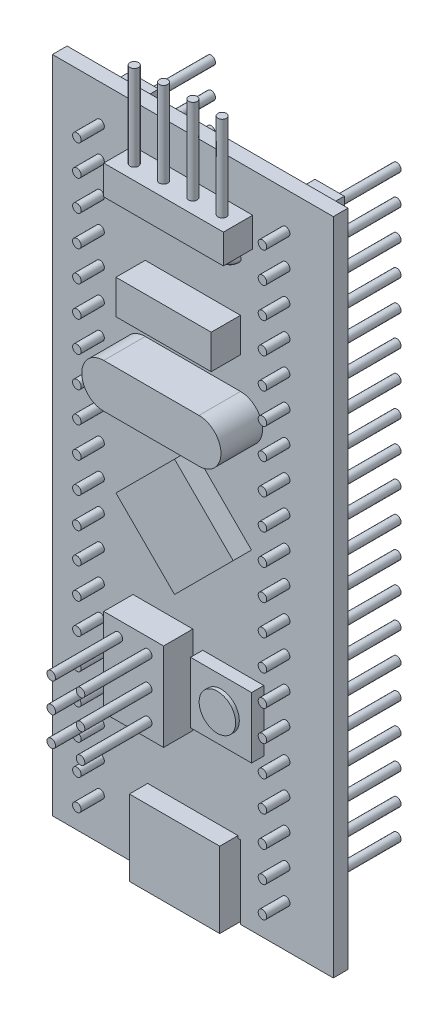
SolidWorks part; units mm, degrees
material "Плата обработки данных, простая"
ref_plane "Спереди" through (0, 0, 0) normal (0, 0, 1) x (1, 0, 0)
ref_plane "Сверху" through (0, 0, 0) normal (0, 1, 0) x (1, 0, 0)
ref_plane "Справа" through (0, 0, 0) normal (1, 0, 0) x (0, 0, -1)
sketch "Эскиз1" plane through (0, 0, 0) normal (0, 0, 1) x (1, 0, 0)
  line L0 (0.4001, -30.8708) -> (0.4001, 23.1292) construction
  line L1 (-11.0999, 23.1292) -> (11.9001, 23.1292)
  line L2 (-11.0999, 23.1292) -> (-11.0999, -30.8708)
  line L3 (-11.0999, -30.8708) -> (11.9001, -30.8708)
  line L4 (11.9001, 23.1292) -> (11.9001, -30.8708)
  line L5 (-11.0999, -3.8708) -> (11.9001, -3.8708) construction
  dimension "D1" = 23
  dimension "D2" = 54
extrude "Бобышка-Вытянуть1" add sketch "Эскиз1" along normal blind 1.2
sketch "Эскиз2" plane through (0, 0, 0) normal (0, 0, -1) x (-1, 0, 0)
  line L0 (-0.4001, 23.1292) -> (-0.4001, -30.8708) construction
  line L1 (-11.9001, 23.1292) -> (11.0999, 23.1292) construction
  line L2 (11.0999, -30.8708) -> (-11.9001, -30.8708) construction
  line L3 (-9.2001, 21.4292) -> (-9.2001, -29.1708)
  line L4 (5.9999, 21.4292) -> (8.3999, 21.4292)
  line L5 (5.9999, 21.4292) -> (5.9999, -29.1708)
  line L6 (5.9999, -29.1708) -> (8.3999, -29.1708)
  line L7 (8.3999, 21.4292) -> (8.3999, -29.1708)
  line L8 (-6.8001, -29.1708) -> (-9.2001, -29.1708)
  line L9 (-6.8001, 21.4292) -> (-6.8001, -29.1708)
  line L10 (-6.8001, 21.4292) -> (-9.2001, 21.4292)
  line L11 (-0.4001, -3.8708) -> (-7.8164, -3.8708) construction
  point P16 (-6.8001, -3.8708)
  dimension "D1" = 2.4
  dimension "D2" = 50.6
  dimension "D3" = 17.6
extrude "Бобышка-Вытянуть2" add sketch "Эскиз2" along normal blind 2.4
sketch "Эскиз3" plane through (0, 0, -2.4) normal (0, 0, -1) x (-1, 0, 0)
  circle A0 centre (-8.0001, 20.1329) radius 0.35
  circle A1 centre (7.1999, 20.1329) radius 0.35
  circle A2 centre (7.1999, 17.6329) radius 0.35
  circle A3 centre (7.1999, 15.1329) radius 0.35
  circle A4 centre (7.1999, 12.6329) radius 0.35
  circle A5 centre (7.1999, 10.1329) radius 0.35
  circle A6 centre (7.1999, 7.6329) radius 0.35
  circle A7 centre (7.1999, 5.1329) radius 0.35
  circle A8 centre (7.1999, 2.6329) radius 0.35
  circle A9 centre (7.1999, 0.1329) radius 0.35
  circle A10 centre (7.1999, -2.3671) radius 0.35
  circle A11 centre (7.1999, -4.8671) radius 0.35
  circle A12 centre (7.1999, -7.3671) radius 0.35
  circle A13 centre (7.1999, -9.8671) radius 0.35
  circle A14 centre (7.1999, -12.3671) radius 0.35
  circle A15 centre (7.1999, -14.8671) radius 0.35
  circle A16 centre (7.1999, -17.3671) radius 0.35
  circle A17 centre (7.1999, -19.8671) radius 0.35
  circle A18 centre (7.1999, -22.3671) radius 0.35
  circle A19 centre (7.1999, -24.8671) radius 0.35
  circle A20 centre (7.1999, -27.3671) radius 0.35
  circle A21 centre (-8.0001, 17.6329) radius 0.35
  circle A22 centre (-8.0001, 15.1329) radius 0.35
  circle A23 centre (-8.0001, 12.6329) radius 0.35
  circle A24 centre (-8.0001, 10.1329) radius 0.35
  circle A25 centre (-8.0001, 7.6329) radius 0.35
  circle A26 centre (-8.0001, 5.1329) radius 0.35
  circle A27 centre (-8.0001, 2.6329) radius 0.35
  circle A28 centre (-8.0001, 0.1329) radius 0.35
  circle A29 centre (-8.0001, -2.3671) radius 0.35
  circle A30 centre (-8.0001, -4.8671) radius 0.35
  circle A31 centre (-8.0001, -7.3671) radius 0.35
  circle A32 centre (-8.0001, -9.8671) radius 0.35
  circle A33 centre (-8.0001, -12.3671) radius 0.35
  circle A34 centre (-8.0001, -14.8671) radius 0.35
  circle A35 centre (-8.0001, -17.3671) radius 0.35
  circle A36 centre (-8.0001, -19.8671) radius 0.35
  circle A37 centre (-8.0001, -22.3671) radius 0.35
  circle A38 centre (-8.0001, -24.8671) radius 0.35
  circle A39 centre (-8.0001, -27.3671) radius 0.35
  dimension "D1" = 0.7
  dimension "D2" = 2
  dimension "D3" = 20
extrude "Бобышка-Вытянуть3" add sketch "Эскиз3" along normal mid plane 11
sketch "Эскиз4" plane through (0, 0, 1.2) normal (0, 0, 1) x (1, 0, 0)
  line L0 (0.4001, 23.1292) -> (0.4001, -30.8708) construction
  line L1 (-4.4999, 19.9292) -> (5.3001, 19.9292)
  line L2 (-4.4999, 19.9292) -> (-4.4999, 17.5292)
  line L3 (-4.4999, 17.5292) -> (5.3001, 17.5292)
  line L4 (5.3001, 19.9292) -> (5.3001, 17.5292)
  line L5 (-4.4999, -11.8708) -> (0.4001, -11.8708)
  line L6 (-4.4999, -11.8708) -> (-4.4999, -19.0708)
  line L7 (-4.4999, -19.0708) -> (0.4001, -19.0708)
  line L8 (0.4001, -11.8708) -> (0.4001, -19.0708)
  line L9 (-3.4999, 12.3292) -> (4.3001, 12.3292)
  line L10 (-3.4999, 12.3292) -> (-3.4999, 9.5292)
  line L11 (-3.4999, 9.5292) -> (4.3001, 9.5292)
  line L12 (4.3001, 12.3292) -> (4.3001, 9.5292)
  line L13 (11.9001, 23.1292) -> (-11.0999, 23.1292) construction
  line L14 (-11.0999, -30.8708) -> (11.9001, -30.8708) construction
  point P18 (5.3001, 18.7292)
  dimension "D1" = 2.4
  dimension "D2" = 4.9
  dimension "D3" = 4.9
  dimension "D4" = 4.9
  dimension "D5" = 7.8
  dimension "D6" = 3.9
  dimension "D7" = 5.6
  dimension "D8" = 10.4
  dimension "D9" = 2.8
  dimension "D10" = 19
  dimension "D11" = 7.2
extrude "Бобышка-Вытянуть4" add sketch "Эскиз4" along normal blind 2.4
sketch "Эскиз5" plane through (0, 19.9292, 0) normal (0, 1, 0) x (1, 0, 0)
  line L0 (5.3001, -3.6) -> (-4.4999, -3.6) construction
  circle A0 centre (-3.1999, -2.4) radius 0.35
  circle A1 centre (-0.7999, -2.4) radius 0.35
  circle A2 centre (1.6001, -2.4) radius 0.35
  circle A3 centre (4.0001, -2.4) radius 0.35
  point P4 (0.4001, -3.6)
  dimension "D1" = 0.7
  dimension "D2" = 3.6
  dimension "D3" = 4
extrude "Бобышка-Вытянуть5" add sketch "Эскиз5" along normal blind 7
sketch "Эскиз6" plane through (0, 17.5292, 0) normal (0, -1, 0) x (1, 0, 0)
  line L0 (0.4001, 3.6) -> (0.4001, 1.2) construction
  line L1 (-4.4999, 1.2) -> (5.3001, 1.2) construction
  circle A0 centre (-3.1999, 2.4) radius 0.35
  circle A1 centre (-0.7999, 2.4) radius 0.35
  circle A2 centre (1.6001, 2.4) radius 0.35
  circle A3 centre (4.0001, 2.4) radius 0.35
  dimension "D1" = 0.7
  dimension "D2" = 3.6
  dimension "D3" = 4
revolve "Повернуть1" add sketch "Эскиз6" angle 360 about L1
sketch "Эскиз7" plane through (0, 0, 3.6) normal (0, 0, 1) x (1, 0, 0)
  line L0 (-4.4999, -11.8708) -> (-4.4999, -19.0708) construction
  line L1 (0.4001, -11.8708) -> (-4.4999, -11.8708) construction
  circle A0 centre (-3.2999, -13.0708) radius 0.35
  circle A1 centre (-0.8999, -13.0708) radius 0.35
  circle A2 centre (-0.8999, -15.4708) radius 0.35
  circle A3 centre (-0.8999, -17.8708) radius 0.35
  circle A4 centre (-3.2999, -15.4708) radius 0.35
  circle A5 centre (-3.2999, -17.8708) radius 0.35
  dimension "D1" = 0.7
  dimension "D2" = 1.2
  dimension "D3" = 1.2
  dimension "D4" = 2
  dimension "D5" = 3
extrude "Бобышка-Вытянуть6" add sketch "Эскиз7" along normal mid plane 11
sketch "Эскиз8" plane through (0, 0, 1.2) normal (0, 0, 1) x (1, 0, 0)
  line L0 (0.4001, 23.1292) -> (0.4001, -30.8708) construction
  line L1 (11.9001, 23.1292) -> (-11.0999, 23.1292) construction
  line L2 (-11.0999, -30.8708) -> (11.9001, -30.8708) construction
  line L3 (-11.0999, -3.8708) -> (11.9001, -3.8708) construction
  line L4 (-11.0999, 23.1292) -> (-11.0999, -30.8708) construction
  line L5 (11.9001, -30.8708) -> (11.9001, 23.1292) construction
  line L6 (-4.3999, -3.8708) -> (0.4001, 0.9292)
  line L7 (0.4001, 0.9292) -> (5.2001, -3.8708)
  line L8 (5.2001, -3.8708) -> (0.4001, -8.6708)
  line L9 (0.4001, -8.6708) -> (-4.3999, -3.8708)
  line L11 (-3.2999, -30.8708) -> (4.1001, -30.8708)
  line L12 (-3.2999, -30.8708) -> (-3.2999, -24.6708)
  line L13 (-3.2999, -24.6708) -> (4.1001, -24.6708)
  line L14 (4.1001, -30.8708) -> (4.1001, -24.6708)
  point P20 (0.4001, -24.6708)
  dimension "D1" = 45
  dimension "D2" = 4.8
  dimension "D3" = 7.4
  dimension "D4" = 6.2
extrude "Бобышка-Вытянуть7" add sketch "Эскиз8" along normal blind 1.5
sketch "Эскиз9" plane through (0, 0, 1.2) normal (0, 0, 1) x (1, 0, 0)
  line L0 (-3.4999, 5.1292) -> (4.3001, 5.1292) construction
  line L1 (-3.4999, 6.9292) -> (4.3001, 6.9292)
  line L2 (-3.4999, 3.3292) -> (4.3001, 3.3292)
  line L3 (4.3001, 12.3292) -> (-3.4999, 12.3292) construction
  arc A0 (-3.4999, 6.9292) -> (-3.4999, 3.3292) centre (-3.4999, 5.1292) ccw
  arc A1 (4.3001, 3.3292) -> (4.3001, 6.9292) centre (4.3001, 5.1292) ccw
  point P2 (0.4001, 5.1292)
  dimension "D1" = 3.6
  dimension "D2" = 9
extrude "Бобышка-Вытянуть8" add sketch "Эскиз9" along normal blind 3.4
sketch "Эскиз10" plane through (0, 0, 1.2) normal (0, 0, 1) x (1, 0, 0)
  line L1 (1.2093, -12.9708) -> (6.2093, -12.9708)
  line L2 (1.2093, -12.9708) -> (1.2093, -17.9708)
  line L3 (1.2093, -17.9708) -> (6.2093, -17.9708)
  line L4 (6.2093, -12.9708) -> (6.2093, -17.9708)
  circle A0 centre (3.7093, -15.4708) radius 2.5 construction
  dimension "D1" = 5
extrude "Бобышка-Вытянуть9" add sketch "Эскиз10" along normal blind 1
sketch "Эскиз11" plane through (0, 0, 2.2) normal (0, 0, 1) x (1, 0, 0)
  circle A0 centre (3.7093, -15.4708) radius 1.4951
extrude "Бобышка-Вытянуть10" add sketch "Эскиз11" along normal blind 0.3
sketch "Эскиз12" plane through (0, -30.8708, 0) normal (0, -1, 0) x (1, 0, 0)
  line L0 (-3.484, 1.2) -> (-3.484, 0)
  line L1 (-4.4999, 1.2) -> (0.4001, 1.2) construction
  line L2 (-11.0999, 0) -> (11.9001, 0) construction
  line L4 (-2.7206, 0.1855) -> (-3.2999, 0.727)
  line L5 (-3.2999, 0.727) -> (-3.2999, 1.2)
  line L6 (-3.2999, 1.2) -> (-3.484, 1.2)
  line L7 (0.4001, 0) -> (0.4001, 2.7) construction
  line L8 (-3.2999, 2.7) -> (4.1001, 2.7) construction
  line L9 (4.1001, 0.727) -> (4.1001, 1.2)
  line L10 (3.5208, 0.1855) -> (4.1001, 0.727)
  line L12 (4.2842, 1.2) -> (4.2842, 0)
  line L13 (4.1001, 1.2) -> (4.2842, 1.2)
  line L14 (-2.7206, 0.1855) -> (3.5208, 0.1855)
  line L15 (4.2842, 0) -> (-3.484, 0)
extrude "Вырез-Вытянуть1" cut sketch "Эскиз12" against normal blind 6
sketch "Çizim1" plane through (0, -30.8708, 0) normal (0, -1, 0) x (1, 0, 0)
  line L0 (-3.0499, 0.9855) -> (-2.5334, 0.4855)
  line L1 (-2.5334, 0.4855) -> (3.3336, 0.4855)
  line L2 (3.3336, 0.4855) -> (3.8501, 0.9855)
  line L3 (3.8501, 0.9855) -> (-3.0499, 0.9855)
  line L4 (-3.0499, 1.3855) -> (-3.0499, 2.3855)
  line L5 (-3.0499, 2.3855) -> (3.8501, 2.3855)
  line L6 (3.8501, 2.3855) -> (3.8501, 1.3855)
  line L7 (3.8501, 1.3855) -> (-3.0499, 1.3855)
  line L8 (-2.7206, 0.1855) -> (-3.2999, 0.727) construction
  line L9 (4.1001, 0.727) -> (3.5208, 0.1855) construction
  line L10 (3.5208, 0.1855) -> (-2.7206, 0.1855) construction
  line L11 (-3.2999, 2.7) -> (-3.2999, 0.727) construction
  line L12 (4.1001, 1.2) -> (4.1001, 0.727) construction
  point P18 (0, 0)
  point P19 (0, 0)
  dimension "D1" = 1
  dimension "D2" = 1
  dimension "D3" = 0.3
  dimension "D4" = 0.5
  dimension "D5" = 0.25
  dimension "D6" = 0.25
  dimension "D7" = 1
  dimension "D8" = 0.4
extrude "Kes-Ekstrüzyon1" cut sketch "Çizim1" against normal blind 5
